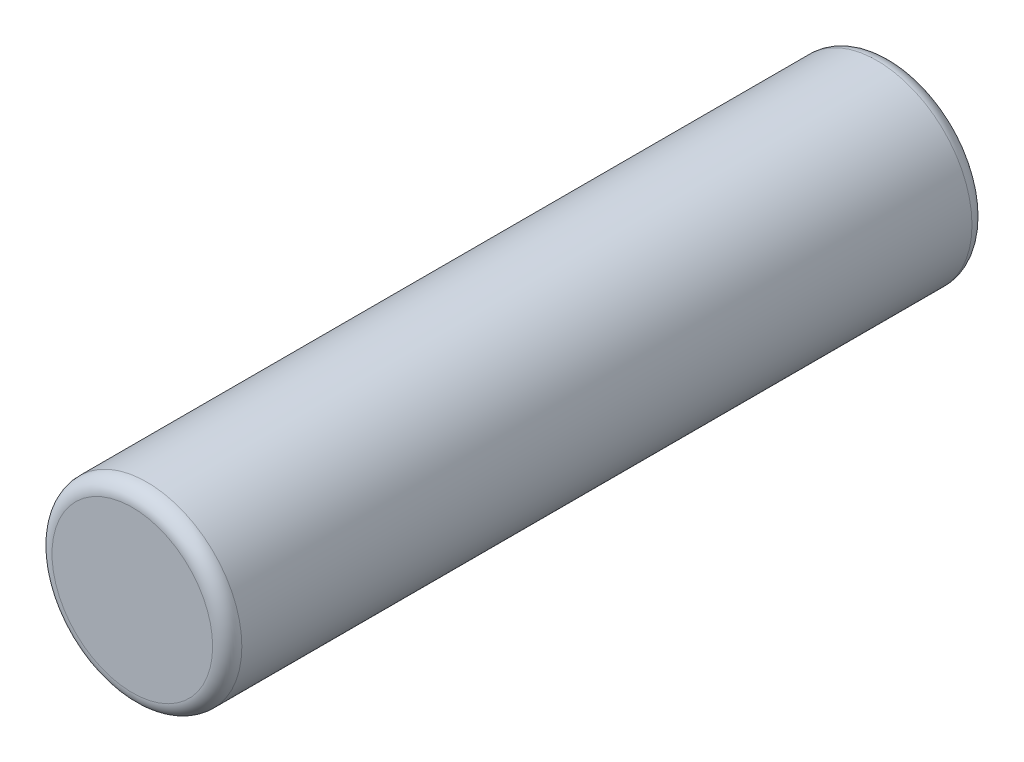
SolidWorks part; units mm, degrees
ref_plane "Front Plane" through (0, 0, 0) normal (0, 0, 1) x (1, 0, 0)
ref_plane "Top Plane" through (0, 0, 0) normal (0, 1, 0) x (1, 0, 0)
ref_plane "Right Plane" through (0, 0, 0) normal (1, 0, 0) x (0, 0, -1)
sketch "Sketch1" plane through (0, 0, 0) normal (0, 0, 1) x (1, 0, 0)
  circle A0 centre (0, 0) radius 1.625
  dimension "D1" = 3.25
extrude "Boss-Extrude1" add sketch "Sketch1" along normal mid plane 13
fillet "Fillet1" radius 0.25 2 edges at (1.625, 0, -6.5) (1.625, 0, 6.5)
